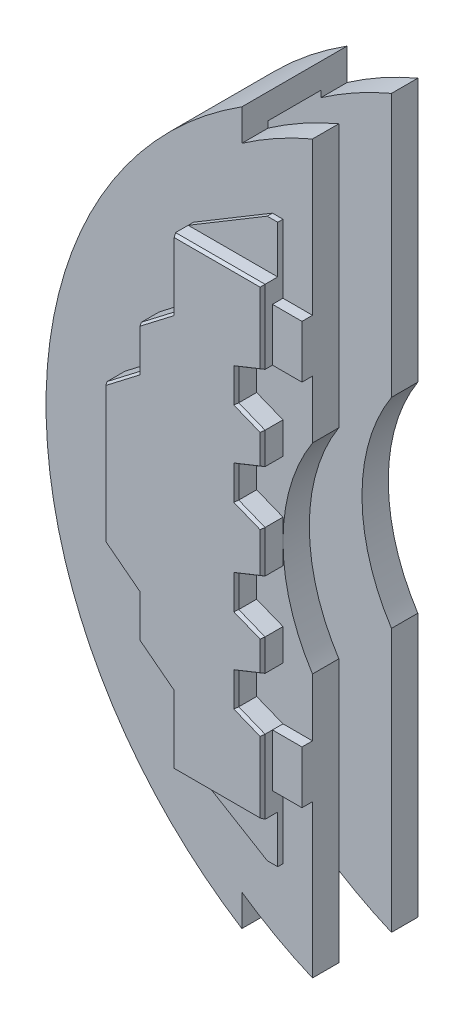
SolidWorks part; units mm, degrees
ref_plane "Front Plane" through (0, 0, 0) normal (0, 0, 1) x (1, 0, 0)
ref_plane "Top Plane" through (0, 0, 0) normal (0, 1, 0) x (1, 0, 0)
ref_plane "Right Plane" through (0, 0, 0) normal (1, 0, 0) x (0, 0, -1)
sketch "Sketch2" plane through (0, 0, 0) normal (0, 0, 1) x (1, 0, 0)
  line L0 (-14.6969, 34.5) -> (-14.6969, 9.5)
  line L1 (-17.5, 0) -> (-40, 0)
  line L2 (-21.4038, 33.7917) -> (-21.4038, 30.7917)
  circle A0 centre (0, 0) radius 37.5 construction
  arc A1 (-14.6969, 9.5) -> (-17.5, 0) centre (0, 0) ccw
  arc A2 (-40, 0) -> (-21.4038, 33.7917) centre (0, 0) cw
  arc A3 (-21.4038, 30.7917) -> (-14.6969, 34.5) centre (0, 0) cw
  point P3 (0, 0)
  point P11 (-13.3351, 11.3324)
  point P13 (-13.1644, 35.1134)
  dimension "D1" = 75
  dimension "D2" = 35
  dimension "D3" = 40
  dimension "D4" = 3
  dimension "D5" = 25
extrude "Boss-Extrude1" add sketch "Sketch2" along normal mid plane 10
sketch "Sketch4" plane through (0, 0, 5) normal (0, 0, 1) x (1, 0, 0)
  line L0 (-17.5, 15) -> (-20, 14)
  line L2 (-17.5, 0) -> (-17.5, 2)
  line L3 (-17.5, 22) -> (-26, 22)
  line L4 (-26, 15.5) -> (-26, 22)
  line L5 (-20, 14) -> (-20, 11)
  line L6 (-20, 11) -> (-17.5, 10)
  line L7 (-17.5, 7) -> (-20, 6)
  line L8 (-20, 6) -> (-20, 3)
  line L9 (-20, 3) -> (-17.5, 2)
  line L10 (-26, 15.5) -> (-29.25, 13)
  line L11 (-29.25, 13) -> (-29.25, 9)
  line L12 (-29.25, 9) -> (-32.5, 6.5)
  line L13 (-32.5, 6.5) -> (-32.5, 0)
  line L14 (-17.5, 7) -> (-17.5, 10)
  line L15 (-17.5, 15) -> (-17.5, 22)
  line L16 (-32.5, 0) -> (-17.5, 0)
  point P3 (0, 0)
  point P15 (-17.5, 12.0881)
  dimension "D1" = 22
  dimension "D2" = 8.5
  dimension "D3" = 7
  dimension "D4" = 2.5
  dimension "D5" = 3
  dimension "D6" = 3
  dimension "D7" = 2
  dimension "D8" = 6.5
  dimension "D9" = 4
  dimension "D10" = 15
  dimension "D11" = 6.5
extrude "Boss-Extrude2" add sketch "Sketch4" along normal blind 2
sketch "Sketch5" plane through (0, 0, 5) normal (0, 0, 1) x (1, 0, 0)
  line L0 (-17.5, 15) -> (-17.5, 22) construction
  line L1 (-17.5, 20) -> (-14.6969, 20)
  line L2 (-17.5, 20) -> (-17.5, 15)
  line L3 (-17.5, 15) -> (-14.6969, 15)
  line L4 (-14.6969, 20) -> (-14.6969, 15)
  line L5 (-14.6969, 9.5) -> (-14.6969, 34.5) construction
  dimension "D1" = 5
  dimension "D2" = 15
extrude "Boss-Extrude3" add sketch "Sketch5" along normal blind 1
sketch "Sketch6" plane through (0, 0, 5) normal (0, 0, 1) x (1, 0, 0)
  line L0 (-26, 22) -> (-18.5, 26.5)
  line L1 (-18.5, 26.5) -> (-17.5, 26.5)
  line L2 (-17.5, 26.5) -> (-17.5, 22)
  line L3 (-17.5, 22) -> (-26, 22) construction
  line L4 (-17.5, 22) -> (-26, 22)
  dimension "D1" = 4.5
  dimension "D2" = 1
extrude "Boss-Extrude4" add sketch "Sketch6" along normal blind 0.5
sketch "Sketch7" plane through (0, 0, 0) normal (1, 0, 0) x (0, 0, -1)
  line L0 (-2.5, 0) -> (2.5, 0)
  line L2 (-2.5, 0) -> (-2.5, 38)
  line L3 (-2.5, 38) -> (2.5, 38)
  line L4 (2.5, 0) -> (2.5, 38)
  line L5 (0, 0) -> (2.5, 38) construction
  line L6 (-2.5, 38) -> (0, 0) construction
  line L7 (0, 0) -> (0, 3.8713) construction
  point P0 (0, 0)
  dimension "D1" = 38
  dimension "D2" = 5
revolve "Cut-Revolve1" cut sketch "Sketch7" angle 360 about L0
mirror "Mirror1" about plane through (0, 0, 0) normal (0, 1, 0) of bodies 105
chamfer "Chamfer1" distance 0.3 angle 30 28 edges at (-30.875, 7.75, 7) (-29.25, 11, 7) (-27.625, 14.25, 7) (-26, 18.75, 7) (-21.75, 22, 7) (-17.5, 18.5, 7) (-18.75, 14.5, 7) (-20, 12.5, 7) (-18.75, 10.5, 7) (-17.5, 8.5, 7) (-18.75, 6.5, 7) (-20, 4.5, 7) (-18.75, 2.5, 7) (-17.5, 0, 7) (-18.75, -2.5, 7) (-20, -4.5, 7) (-18.75, -6.5, 7) (-17.5, -8.5, 7) (-18.75, -10.5, 7) (-20, -12.5, 7) (-18.75, -14.5, 7) (-17.5, -18.5, 7) (-21.75, -22, 7) (-26, -18.75, 7) (-27.625, -14.25, 7) (-29.25, -11, 7) (-30.875, -7.75, 7) (-32.5, 0, 7)
